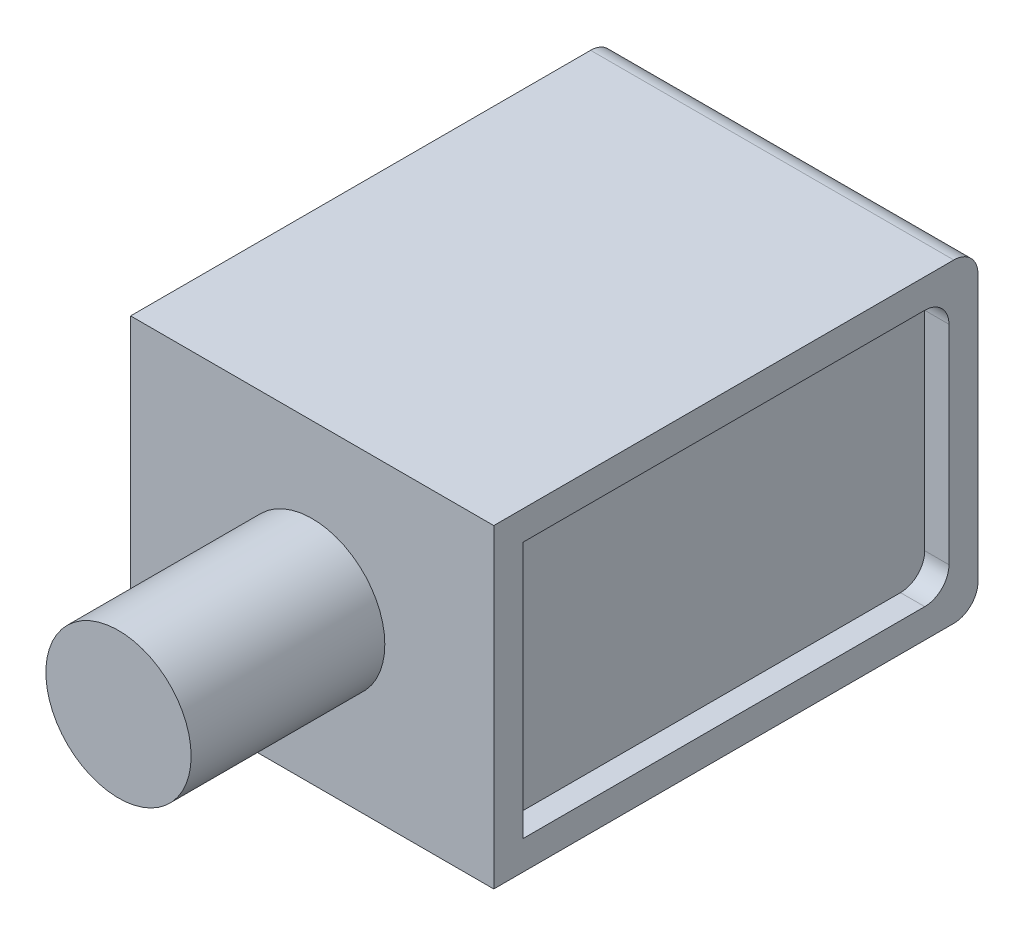
SolidWorks part; units mm, degrees
ref_plane "Plan de face" through (0, 0, 0) normal (0, 0, 1) x (1, 0, 0)
ref_plane "Plan de dessus" through (0, 0, 0) normal (0, 1, 0) x (1, 0, 0)
ref_plane "Plan de droite" through (0, 0, 0) normal (1, 0, 0) x (0, 0, -1)
sketch "Esquisse1" plane through (0, 0, 0) normal (0, 0, 1) x (1, 0, 0)
  line L1 (7.5, -6.5) -> (-7.5, -6.5)
  line L2 (7.5, -6.5) -> (7.5, 6.5)
  line L3 (7.5, 6.5) -> (-7.5, 6.5)
  line L4 (-7.5, -6.5) -> (-7.5, 6.5)
  line L5 (7.5, -6.5) -> (-7.5, 6.5) construction
  line L6 (7.5, 6.5) -> (-7.5, -6.5) construction
  point P0 (0, 0)
  dimension "D1" = 13
  dimension "D2" = 15
extrude "Boss.-Extru.1" add sketch "Esquisse1" along normal mid plane 20
fillet "Congé1" radius 1 2 edges at (0, -6.5, -10) (0, 6.5, -10)
sketch "Esquisse2" plane through (7.5, 0, 0) normal (1, 0, 0) x (0, 0, -1)
  line L8 (-8.8, -5.3) -> (8.8, -5.3)
  line L9 (8.8, -5.3) -> (8.8, 5.3)
  line L10 (8.8, 5.3) -> (-8.8, 5.3)
  line L11 (-8.8, 5.3) -> (-8.8, -5.3)
  line L12 (-8.8, -5.3) -> (8.8, -5.3)
  line L13 (8.8, -5.3) -> (8.8, 5.3)
  line L14 (8.8, 5.3) -> (-8.8, 5.3)
  line L15 (-8.8, 5.3) -> (-8.8, -5.3)
  dimension "D1" = 1.2
extrude "Enlèv. mat.-Extru.1" cut sketch "Esquisse2" against normal blind 1
fillet "Congé2" radius 1 2 edges at (7, -5.3, -8.8) (7, 5.3, -8.8)
mirror "Symétrie1" about plane through (0, 0, 0) normal (1, 0, 0) of "Congé2", "Enlèv. mat.-Extru.1"
sketch "Esquisse3" plane through (0, 0, 10) normal (0, 0, 1) x (1, 0, 0)
  circle A0 centre (0, 0) radius 3
  dimension "D1" = 6
extrude "Boss.-Extru.2" add sketch "Esquisse3" along normal blind 8
